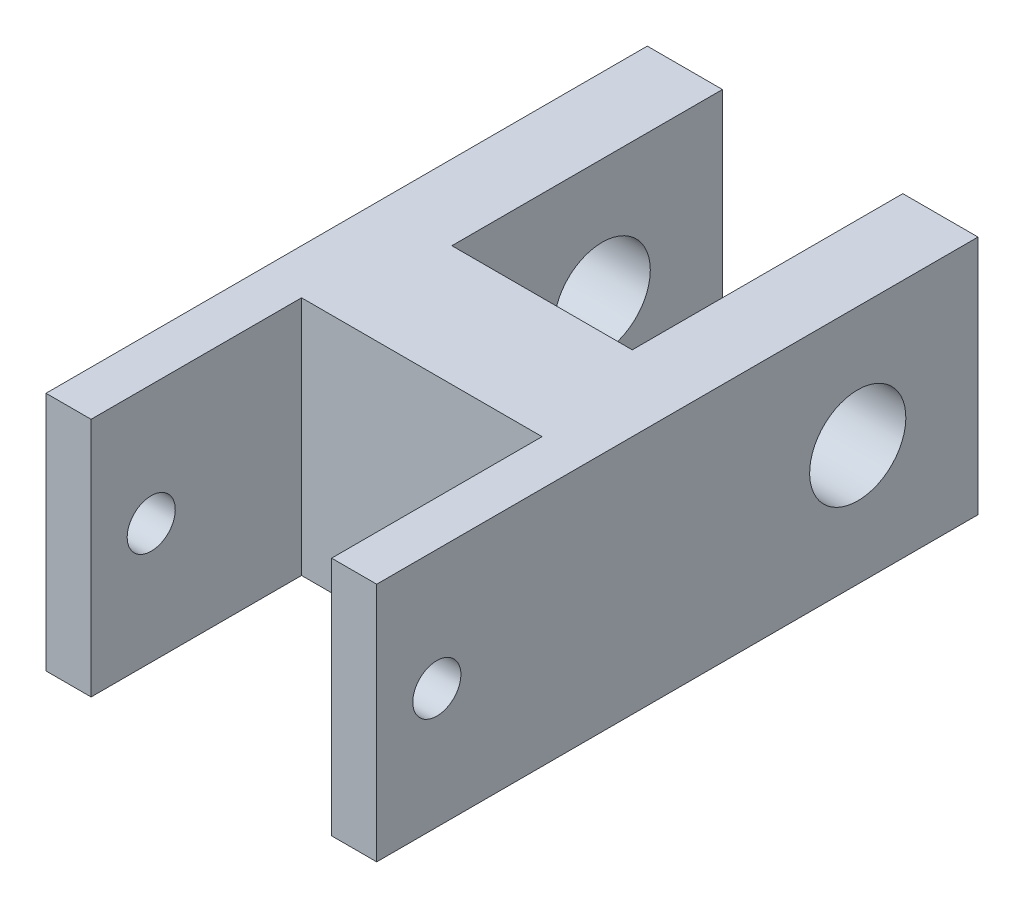
SolidWorks part; units mm, degrees
material "6063-T6"
ref_plane "Front Plane" through (0, 0, 0) normal (0, 0, 1) x (1, 0, 0)
ref_plane "Top Plane" through (0, 0, 0) normal (0, 1, 0) x (1, 0, 0)
ref_plane "Right Plane" through (0, 0, 0) normal (1, 0, 0) x (0, 0, -1)
sketch "Sketch1" plane through (0, 0, 0) normal (0, 0, 1) x (1, 0, 0)
  line L1 (0, 0) -> (55, 0)
  line L2 (0, 0) -> (0, 40)
  line L3 (0, 40) -> (55, 40)
  line L4 (55, 0) -> (55, 40)
  dimension "D1" = 40
  dimension "D2" = 55
extrude "Boss-Extrude1" add sketch "Sketch1" along normal blind 100
sketch "Sketch2" plane through (0, 0, 100) normal (0, 0, 1) x (1, 0, 0)
  line L5 (0, 0) -> (55, 0) construction
  line L6 (7.5, 0) -> (47.5, 0)
  line L7 (7.5, 0) -> (7.5, 40)
  line L9 (47.5, 0) -> (47.5, 40)
  line L10 (0, 40) -> (0, 0) construction
  line L11 (55, 40) -> (0, 40) construction
  line L12 (7.5, 40) -> (47.5, 40)
  dimension "D1" = 40
  dimension "D2" = 7.5
extrude "Cut-Extrude1" cut sketch "Sketch2" against normal blind 35
sketch "Sketch3" plane through (55, 0, 0) normal (1, 0, 0) x (0, 0, -1)
  line L0 (-100, 0) -> (-100, 40) construction
  line L1 (-100, 40) -> (0, 40) construction
  line L2 (0, 0) -> (0, 40) construction
  circle A0 centre (-90, 20) radius 4
  circle A1 centre (-20, 20) radius 8
  dimension "D1" = 8
  dimension "D2" = 10
  dimension "D3" = 20
  dimension "D4" = 16
  dimension "D5" = 20
  dimension "D6" = 20
extrude "Cut-Extrude2" cut sketch "Sketch3" against normal through all
sketch "Sketch4" plane through (0, 0, 0) normal (0, 0, -1) x (-1, 0, 0)
  line L0 (-55, 40) -> (0, 40) construction
  line L1 (-42.5, 40) -> (-12.5, 40)
  line L2 (-42.5, 40) -> (-42.5, 0)
  line L3 (-42.5, 0) -> (-12.5, 0)
  line L4 (-12.5, 40) -> (-12.5, 0)
  line L5 (0, 0) -> (-55, 0) construction
  line L6 (-55, 0) -> (-55, 40) construction
  dimension "D1" = 30
  dimension "D2" = 12.5
extrude "Cut-Extrude3" cut sketch "Sketch4" against normal blind 45
